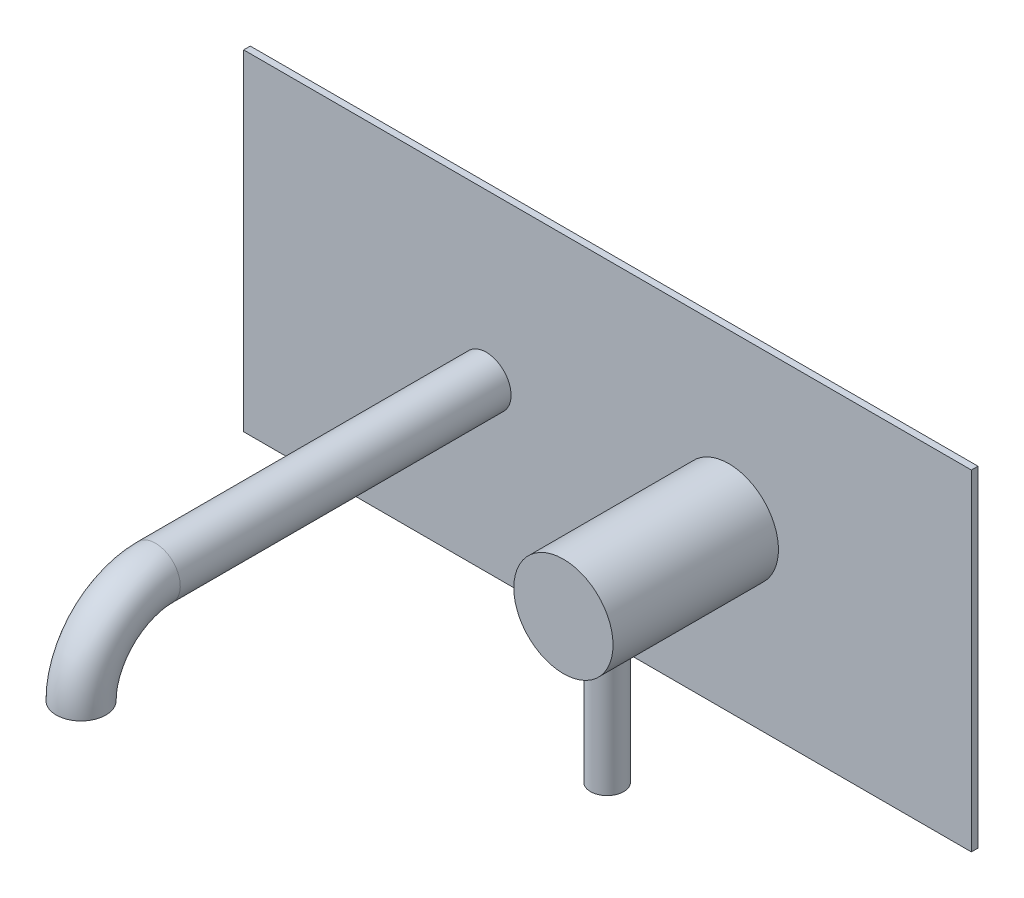
SolidWorks part; units mm, degrees
ref_plane "Спереди" through (0, 0, 0) normal (0, 0, 1) x (1, 0, 0)
ref_plane "Сверху" through (0, 0, 0) normal (0, 1, 0) x (1, 0, 0)
ref_plane "Справа" through (0, 0, 0) normal (1, 0, 0) x (0, 0, -1)
other "Configuration Table"
sketch "Эскиз1" plane through (0, 0, 0) normal (0, 0, 1) x (1, 0, 0)
  line L1 (0, 0) -> (220, 0)
  line L2 (0, 0) -> (0, 100)
  line L3 (0, 100) -> (220, 100)
  line L4 (220, 0) -> (220, 100)
  dimension "D1" = 220
  dimension "D2" = 100
extrude "Бобышка-Вытянуть1" add sketch "Эскиз1" along normal blind 2
sketch3d "Трехмерный эскиз1"
  line L0 (73.3333, 50, 2) -> (73.3333, 50, 102)
  line L1 (0, 50, 2) -> (73.3333, 50, 2) construction
  line L2 (0, 100, 2) -> (0, 0, 2) construction
  line L3 (73.3333, 50, 2) -> (146.6667, 50, 2) construction
  line L4 (73.3333, 27.5, 102) -> (73.3333, 50, 102) construction
  line L5 (73.3333, 27.5, 124.5) -> (73.3333, 27.5, 102) construction
  line L7 (146.6667, 50, 2) -> (220, 50, 2) construction
  line L8 (220, 0, 2) -> (220, 100, 2) construction
  circle A0 centre (73.3333, 27.5, 102) radius 22.5 construction
  arc A1 (73.3333, 50, 102) -> (73.3333, 27.5, 124.5) centre (73.3333, 27.5, 102) cw
  point P11 (95.8333, 27.5, 102)
  point P12 (95.8333, 27.5, 102)
  point P16 (146.6667, 50, 48.6278)
  dimension "D1" = 45
  dimension "D2" = 100
sweep "По траектории1" add path "Трехмерный эскиз1" circular profile diameter 15 parameters "D3"=15
sketch "Эскиз15" plane through (0, 0, 2) normal (0, 0, 1) x (1, 0, 0)
  line L0 (73.3333, 50) -> (146.6667, 50) construction
  line L1 (146.6667, 50) -> (220, 50) construction
  line L2 (220, 0) -> (220, 100) construction
  circle A0 centre (146.6667, 50) radius 15
  dimension "D1" = 30
extrude "Бобышка-Вытянуть2" add sketch "Эскиз15" along normal blind 50
ref_plane "Плоскость1" through (0, 50, 0) normal (0, -1, 0) x (-1, 0, 0)
sketch "Эскиз16" plane through (0, 50, 0) normal (0, -1, 0) x (-1, 0, 0)
  line L0 (-146.6667, -52) -> (-146.6667, -38.789) construction
  line L1 (-161.6667, -52) -> (-131.6667, -52) construction
  circle A0 centre (-146.6667, -38.789) radius 5
  point P0 (-146.6667, -38.789)
  point P6 (-146.6667, -45.9829)
  dimension "D1" = 10
extrude "Бобышка-Вытянуть3" add sketch "Эскиз16" along normal blind 50
